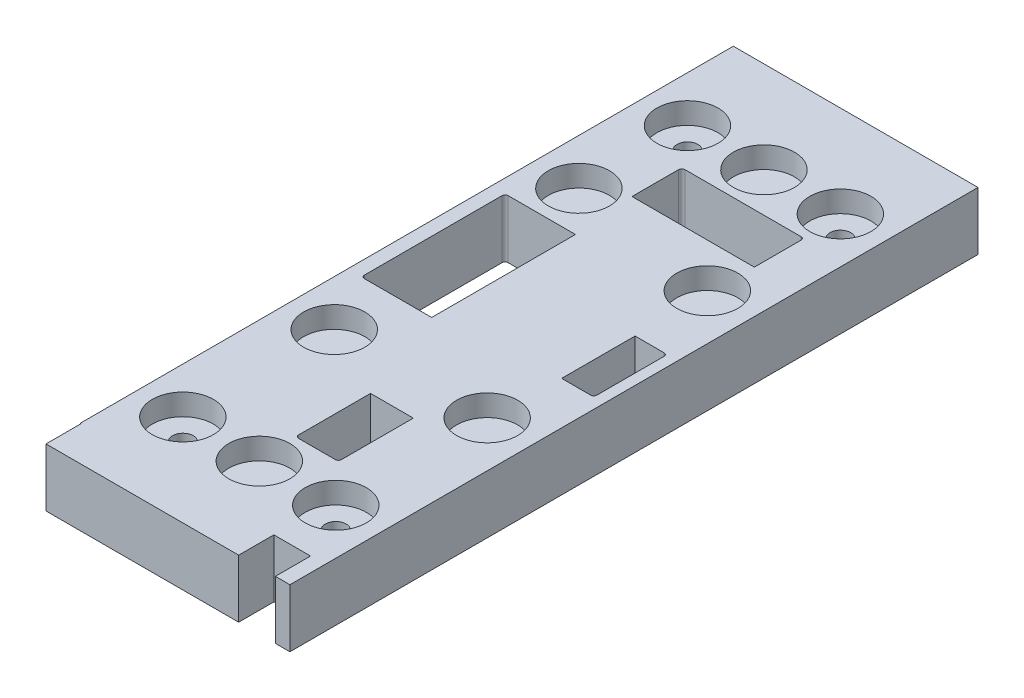
SolidWorks part; units mm, degrees
material "Plain Carbon Steel"
ref_plane "Front Plane" through (0, 0, 0) normal (0, 0, 1) x (1, 0, 0)
ref_plane "Top Plane" through (0, 0, 0) normal (0, 1, 0) x (1, 0, 0)
ref_plane "Right Plane" through (0, 0, 0) normal (1, 0, 0) x (0, 0, -1)
sketch "Sketch1" plane through (0, 0, 0) normal (0, 1, 0) x (1, 0, 0)
  line L1 (-40, -112.5) -> (40, -112.5)
  line L2 (-40, -112.5) -> (-40, 112.5)
  line L3 (-40, 112.5) -> (40, 112.5)
  line L4 (40, -112.5) -> (40, 112.5)
  line L5 (-40, -112.5) -> (40, 112.5) construction
  line L6 (-40, 112.5) -> (40, -112.5) construction
  point P0 (0, 0)
  dimension "D1" = 225
  dimension "D2" = 80
extrude "Boss-Extrude1" add sketch "Sketch1" against normal blind 19
sketch "Sketch2" plane through (0, 0, 0) normal (0, 1, 0) x (1, 0, 0)
  line L0 (-34.5, -13.64) -> (-12.5, -13.64) construction
  line L1 (-35.5, 32.36) -> (-35.5, -12.64) construction
  line L2 (-12.5, 33.36) -> (-34.5, 33.36) construction
  line L3 (-12.5, -13.64) -> (-12.5, 33.36) construction
  line L4 (0, -69.64) -> (12, -69.64) construction
  line L5 (-1, -45.14) -> (-1, -68.64) construction
  line L6 (13, -45.14) -> (-1, -45.14) construction
  line L7 (13, -68.64) -> (13, -45.14) construction
  line L8 (35.5, 14.36) -> (26, 14.36) construction
  line L9 (36.5, -8.64) -> (36.5, 13.36) construction
  line L10 (26, -9.64) -> (35.5, -9.64) construction
  line L11 (26, 14.36) -> (26, -9.64) construction
  line L12 (26, 53.36) -> (26, 68.64) construction
  line L13 (-14, 53.36) -> (26, 53.36) construction
  line L14 (-14, 68.64) -> (-14, 53.36) construction
  line L15 (25, 69.64) -> (-13, 69.64) construction
  line L16 (-34.5, -13.64) -> (-12.5, -13.64)
  line L17 (-35.5, 32.36) -> (-35.5, -12.64)
  line L18 (-12.5, 33.36) -> (-34.5, 33.36)
  line L19 (-12.5, -13.64) -> (-12.5, 33.36)
  line L20 (0, -69.64) -> (12, -69.64)
  line L21 (-1, -45.14) -> (-1, -68.64)
  line L22 (13, -45.14) -> (-1, -45.14)
  line L23 (13, -68.64) -> (13, -45.14)
  line L24 (35.5, 14.36) -> (26, 14.36)
  line L25 (36.5, -8.64) -> (36.5, 13.36)
  line L26 (26, -9.64) -> (35.5, -9.64)
  line L27 (26, 14.36) -> (26, -9.64)
  line L28 (26, 53.36) -> (26, 68.64)
  line L29 (-14, 53.36) -> (26, 53.36)
  line L30 (-14, 68.64) -> (-14, 53.36)
  line L31 (25, 69.64) -> (-13, 69.64)
  arc A0 (-35.5, -12.64) -> (-34.5, -13.64) centre (-34.5, -12.64) ccw construction
  arc A1 (-34.5, 33.36) -> (-35.5, 32.36) centre (-34.5, 32.36) ccw construction
  arc A2 (12, -69.64) -> (13, -68.64) centre (12, -68.64) ccw construction
  arc A3 (-1, -68.64) -> (0, -69.64) centre (0, -68.64) ccw construction
  arc A4 (36.5, 13.36) -> (35.5, 14.36) centre (35.5, 13.36) ccw construction
  arc A5 (35.5, -9.64) -> (36.5, -8.64) centre (35.5, -8.64) ccw construction
  arc A6 (26, 68.64) -> (25, 69.64) centre (25, 68.64) ccw construction
  arc A7 (-13, 69.64) -> (-14, 68.64) centre (-13, 68.64) ccw construction
  arc A8 (-35.5, -12.64) -> (-34.5, -13.64) centre (-34.5, -12.64) ccw
  arc A9 (-34.5, 33.36) -> (-35.5, 32.36) centre (-34.5, 32.36) ccw
  arc A10 (12, -69.64) -> (13, -68.64) centre (12, -68.64) ccw
  arc A11 (-1, -68.64) -> (0, -69.64) centre (0, -68.64) ccw
  arc A12 (36.5, 13.36) -> (35.5, 14.36) centre (35.5, 13.36) ccw
  arc A13 (35.5, -9.64) -> (36.5, -8.64) centre (35.5, -8.64) ccw
  arc A14 (26, 68.64) -> (25, 69.64) centre (25, 68.64) ccw
  arc A15 (-13, 69.64) -> (-14, 68.64) centre (-13, 68.64) ccw
extrude "Cut-Extrude1" cut sketch "Sketch2" against normal up to next
sketch "Sketch4" plane through (0, 0, 0) normal (0, 1, 0) x (1, 0, 0)
  circle A0 centre (25, -82.5) radius 10 construction
  circle A1 centre (0, -82.5) radius 10 construction
  circle A2 centre (-25, -82.5) radius 10 construction
  circle A3 centre (-25, -33) radius 10 construction
  circle A4 centre (25, -33) radius 10 construction
  circle A6 centre (25, 39) radius 10 construction
  circle A7 centre (-25, 47) radius 10 construction
  circle A8 centre (-25, 82.5) radius 10 construction
  circle A9 centre (0, 82.5) radius 10 construction
  circle A10 centre (25, 82.5) radius 10 construction
  circle A11 centre (25, -82.5) radius 10
  circle A12 centre (0, -82.5) radius 10
  circle A13 centre (-25, -82.5) radius 10
  circle A14 centre (-25, -33) radius 10
  circle A15 centre (25, -33) radius 10
  circle A17 centre (25, 39) radius 10
  circle A18 centre (-25, 47) radius 10
  circle A19 centre (-25, 82.5) radius 10
  circle A20 centre (0, 82.5) radius 10
  circle A21 centre (25, 82.5) radius 10
extrude "Cut-Extrude2" cut sketch "Sketch4" against normal blind 7
sketch "Sketch5" plane through (0, -19, 0) normal (0, -1, 0) x (1, 0, 0)
  circle A0 centre (6, 100) radius 8.5
  circle A1 centre (6, -100) radius 8.5
  dimension "D1" = 17
extrude "Cut-Extrude3" cut sketch "Sketch5" against normal blind 5
sketch "Sketch7" plane through (0, 0, 0) normal (0, 1, 0) x (1, 0, 0)
  line L0 (-40, -112.5) -> (40, -112.5) construction
  line L1 (23.25, -112.5) -> (35.25, -112.5)
  line L2 (23.25, -112.5) -> (23.25, -101)
  line L3 (23.25, -101) -> (35.25, -101)
  line L4 (35.25, -112.5) -> (35.25, -101)
  line L5 (24.25, -115) -> (24.25, -102.5) construction
  line L6 (34.25, -102.5) -> (34.25, -115) construction
  line L7 (24.75, -102) -> (33.75, -102) construction
  line L8 (-50.25, -102) -> (-41.25, -102) construction
  line L9 (-39.75, -112.5) -> (-40.75, -112.5)
  line L10 (-39.75, -112.5) -> (-39.75, -101)
  line L11 (-39.75, -101) -> (-40.75, -101)
  line L12 (-40.75, -112.5) -> (-40.75, -101)
  line L13 (-40.75, -102.5) -> (-40.75, -115) construction
  dimension "D1" = 1
  dimension "D2" = 1
  dimension "D3" = 1
  dimension "D4" = 1
  dimension "D5" = 1
  dimension "D6" = 1
extrude "Cut-Extrude4" cut sketch "Sketch7" against normal up to next
hole_wizard "M8 Tapped Hole1" positions "Sketch10" profile "Sketch9" tap size "M8" standard "ISO" end condition through all
sketch "Sketch10" plane through (0, 0, 0) normal (0, 1, 0) x (1, 0, 0)
  point P0 (-25, 82.5)
  point P3 (25, 82.5)
  point P6 (25, -82.5)
  point P9 (-25, -82.5)
sketch "Sketch9" plane through (-25, 0, -82.5) normal (1, 0, 0) x (0, 0, 1)
  line L0 (0, 0) -> (0, 19)
  line L1 (0, 19) -> (3.4, 19)
  line L2 (3.4, 19) -> (3.4, 0)
  line L5 (3.4, 0) -> (0, 0)
  line L11 (0, -6.35) -> (0, 107.95) construction
  dimension "Thru Tap Drill Dia." = 6.8
  dimension "Thru Tap Drill Depth" = 19
cosmetic thread "Hole Thread1"
cosmetic thread "Hole Thread2"
cosmetic thread "Hole Thread3"
cosmetic thread "Hole Thread4"
